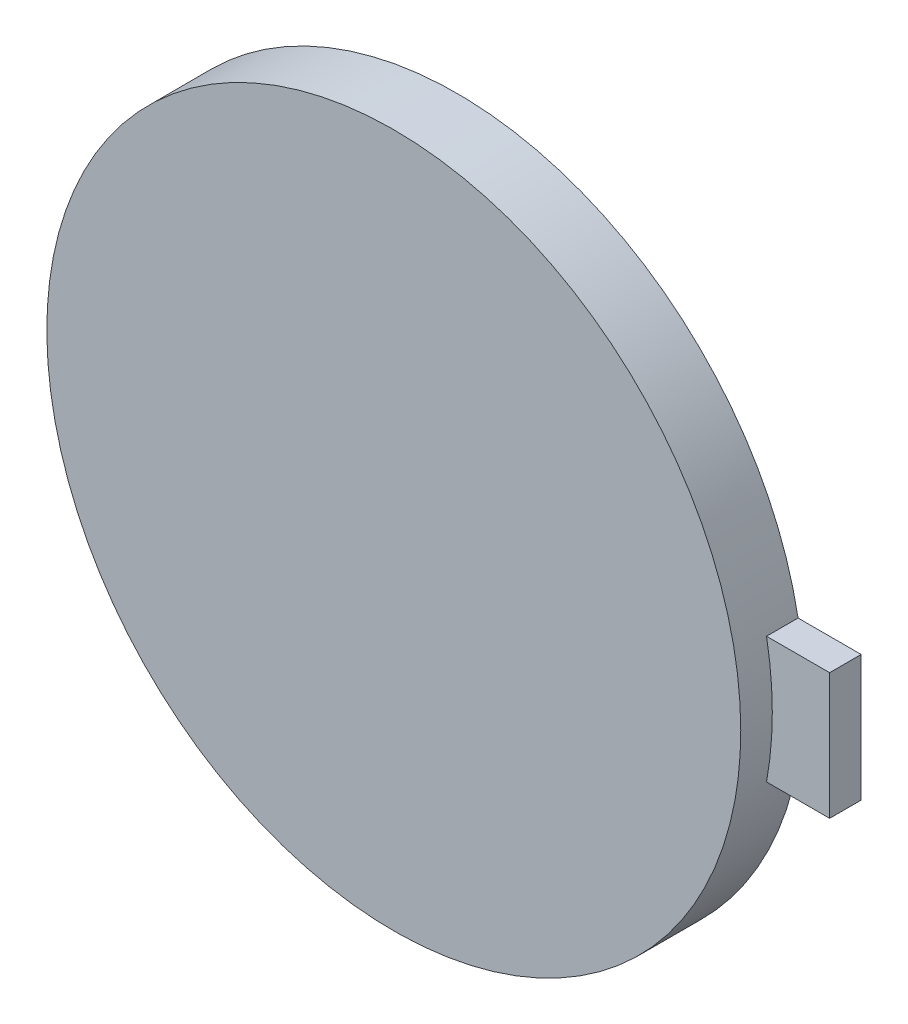
SolidWorks part; units mm, degrees
ref_plane "정면" through (0, 0, 0) normal (0, 0, 1) x (1, 0, 0)
ref_plane "윗면" through (0, 0, 0) normal (0, 1, 0) x (1, 0, 0)
ref_plane "우측면" through (0, 0, 0) normal (1, 0, 0) x (0, 0, -1)
sketch "스케치1" plane through (0, 0, 0) normal (0, 0, 1) x (1, 0, 0)
  circle A0 centre (0, 0) radius 55
  circle A1 centre (0, 0) radius 50
  dimension "D1" = 110
  dimension "D2" = 100
extrude "보스-돌출1" add sketch "스케치1" along normal blind 5
sketch "스케치3" plane through (0, 0, 5) normal (0, 0, 1) x (1, 0, 0)
  circle A0 centre (0, 0) radius 55
  circle A1 centre (0, 0) radius 55 construction
extrude "보스-돌출2" add sketch "스케치3" along normal blind 5
sketch "스케치5" plane through (0, 0, 0) normal (0, 0, 1) x (1, 0, 0)
  line L1 (54.0833, 10) -> (64.0833, 10)
  line L2 (54.0833, 10) -> (54.0833, -10)
  line L3 (54.0833, -10) -> (64.0833, -10)
  line L4 (64.0833, 10) -> (64.0833, -10)
  circle A0 centre (0, 0) radius 55 construction
  point P6 (0, 0)
  point P7 (54.0833, 0)
  dimension "D1" = 20
  dimension "D2" = 10
extrude "보스-돌출3" add sketch "스케치5" along normal blind 10
sketch "스케치6" plane through (0, 0, 10) normal (0, 0, 1) x (1, 0, 0)
  line L0 (54.0833, 10) -> (64.0833, 10)
  line L1 (64.0833, 10) -> (64.0833, -10)
  line L2 (64.0833, -10) -> (54.0833, -10)
  arc A0 (54.0833, 10) -> (54.0833, -10) centre (0, 0) cw
extrude "컷-돌출1" cut sketch "스케치6" against normal blind 5
